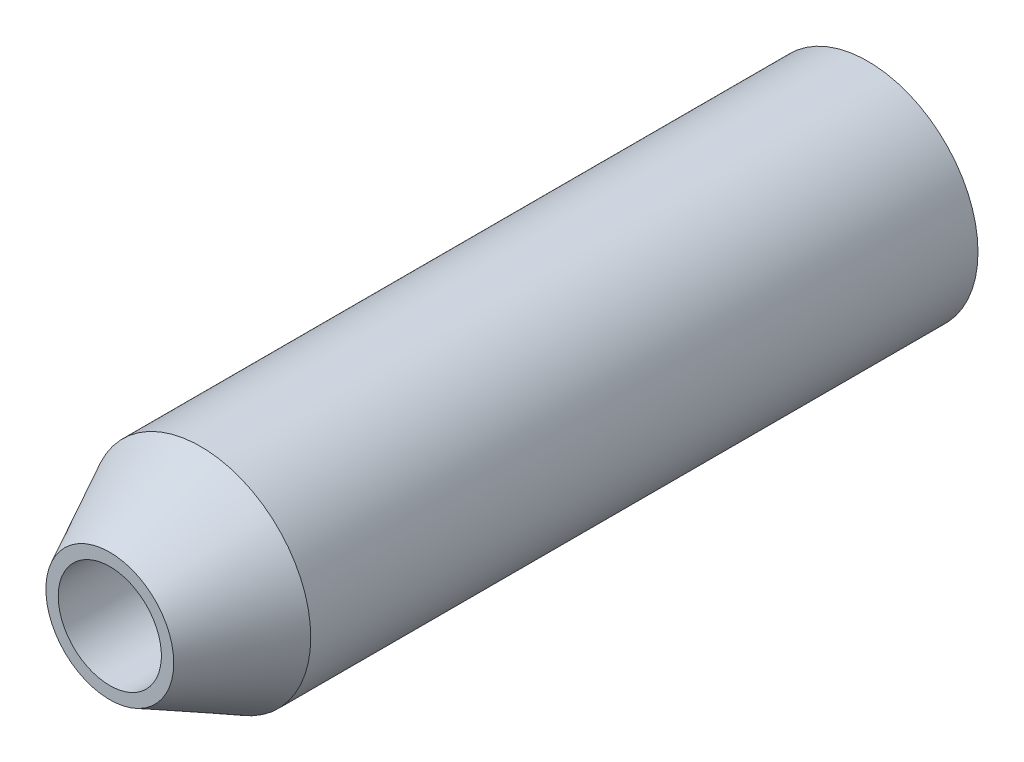
SolidWorks part; units mm, degrees
material "O1 Steel"
ref_plane "Alzado" through (0, 0, 0) normal (0, 0, 1) x (1, 0, 0)
ref_plane "Planta" through (0, 0, 0) normal (0, 1, 0) x (1, 0, 0)
ref_plane "Vista lateral" through (0, 0, 0) normal (1, 0, 0) x (0, 0, -1)
sketch "Croquis3" plane through (0, 0, 0) normal (0, 0, 1) x (1, 0, 0)
  circle A0 centre (0, 0) radius 3.175
  dimension "D1" = 6.35
extrude "Saliente-Extruir2" add sketch "Croquis3" along normal mid plane 21.844
sketch "Croquis5" plane through (0, 0, -10.922) normal (0, 0, -1) x (-1, 0, 0)
  point P0 (0, 0)
hole_wizard "Refrentado para tornillo con cabeza hueca de 1/41" positions "Croquis5" profile "Croquis6" counterbore size "1/4" standard "Ansi Inch" end condition through all
sketch "Croquis6" plane through (0, 0, -10.922) normal (1, 0, 0) x (0, 1, 0)
  line L0 (0, 0) -> (0, 21.844)
  line L1 (0, 21.844) -> (1.4859, 21.844)
  line L3 (1.4859, 21.844) -> (1.4859, 16.637)
  line L4 (1.4859, 16.637) -> (2.3495, 16.637)
  line L5 (2.3495, 16.637) -> (2.3495, 0)
  line L7 (2.3495, 0) -> (0, 0)
  line L11 (0, -6.35) -> (0, 107.95) construction
  dimension "Diámetro de taladro hasta el siguiente" = 2.9718
  dimension "Profundidad de taladro hasta el siguiente" = 21.844
  dimension "Diámetro de refrentado" = 4.699
  dimension "Profundidad de refrentado" = 16.637
sketch "Croquis7" plane through (0, 0, 0) normal (0, 1, 0) x (1, 0, 0)
  line L0 (-3.175, -8.3058) -> (-1.842, -10.922)
  line L1 (-3.175, 10.922) -> (-3.175, -10.922) construction
  line L2 (-3.175, -10.922) -> (3.175, -10.922) construction
  line L3 (-1.842, -10.922) -> (-3.175, -10.922)
  line L4 (-3.175, -10.922) -> (-3.175, -8.3058)
  line L5 (3.175, 10.922) -> (-3.175, 10.922) construction
  line L6 (0, -10.922) -> (0, 0) construction
  dimension "D1" = 27
  dimension "D2" = 19.2278
revolve "Cortar-Revolución1" cut sketch "Croquis7" angle 360 about L6
